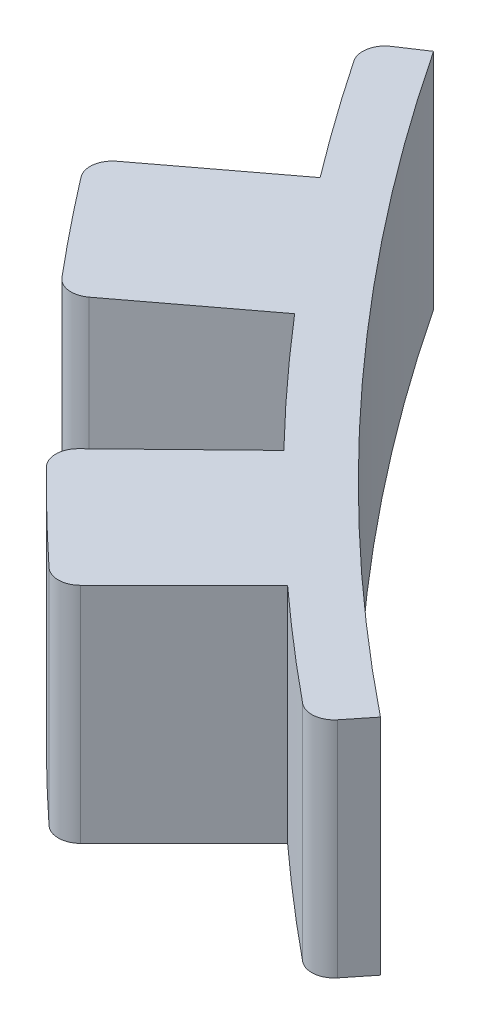
SolidWorks part; units mm, degrees
material "Plain Carbon Steel"
ref_plane "Front Plane" through (0, 0, 0) normal (0, 0, 1) x (1, 0, 0)
ref_plane "Top Plane" through (0, 0, 0) normal (0, 1, 0) x (1, 0, 0)
ref_plane "Right Plane" through (0, 0, 0) normal (1, 0, 0) x (0, 0, -1)
sketch "Sketch1" plane through (0, 0, 0) normal (0, 1, 0) x (1, 0, 0)
  line L0 (0, 0) -> (-260.052, -196.3245)
  line L1 (-248.1361, -211.1843) -> (-232.9055, -199.686)
  line L2 (0, 0) -> (-220.0651, -213.754)
  line L3 (-220.0651, -213.754) -> (-233.7293, -227.0263)
  line L4 (-220.0645, -240.2956) -> (-206.581, -226.8121)
  line L5 (-206.581, -226.8121) -> (-202.5304, -222.3648)
  line L6 (-240.048, -181.2226) -> (-244.8489, -184.8471)
  line L7 (-255.8494, -169.2942) -> (-250.8327, -165.9747)
  line L8 (-192.1057, -239.1963) -> (-188.3389, -234.5061)
  circle A0 centre (0, 0) radius 300.7734
  circle A1 centre (0, 0) radius 325.8379
  circle A2 centre (0, 0) radius 306.7889
  arc A3 (-260.052, -196.3245) -> (-248.1361, -211.1843) centre (0, 0) ccw
  arc A4 (-232.9055, -199.686) -> (-220.0651, -213.754) centre (0, 0) ccw
  arc A5 (-233.7293, -227.0263) -> (-220.0645, -240.2956) centre (0, 0) ccw
  arc A6 (-202.5304, -222.3648) -> (-240.048, -181.2226) centre (0, 0) cw
  arc A7 (-244.8489, -184.8471) -> (-255.8494, -169.2942) centre (0, 0) cw
  arc A8 (-250.8327, -165.9747) -> (-240.048, -181.2226) centre (0, 0) ccw
  arc A9 (-206.581, -226.8121) -> (-192.1057, -239.1963) centre (0, 0) ccw
  dimension "D1" = 19.05
  dimension "D2" = 19.05
  dimension "D3" = 19.05
  dimension "D4" = 19.05
  dimension "D5" = 19.05
extrude "Boss-Extrude1" add sketch "Sketch1" along normal blind 25.4 contours L7 A2 L0 A0 | A2 L0 A1 L1 | L0 A2 L2 A0 | A2 L3 A1 L4 | L2 A2 L5 A0 | L5 A2 L8 A0
fillet "Fillet1" radius 2.54 6 edges at (-192.1057, 12.7, 239.1963) (-220.0645, 12.7, 240.2956) (-233.7293, 12.7, 227.0263) (-248.1361, 12.7, 211.1843) (-260.052, 12.7, 196.3245) (-255.8494, 12.7, 169.2942)
